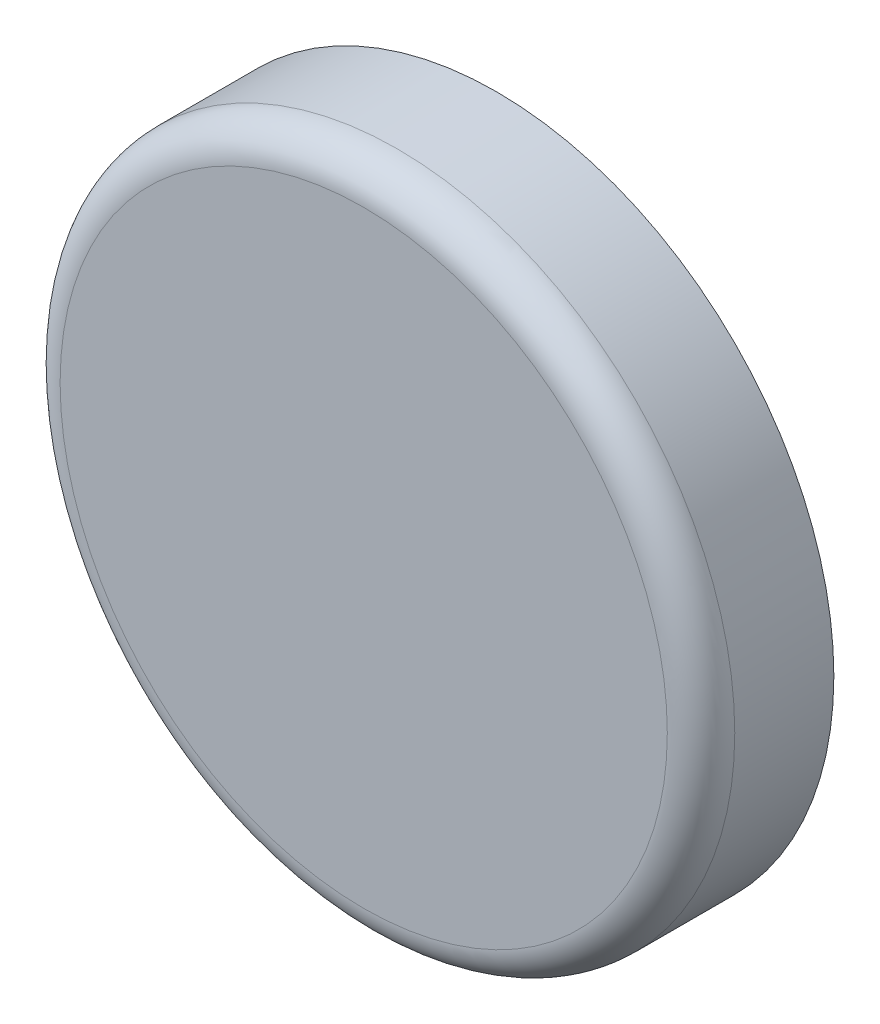
SolidWorks part; units mm, degrees
ref_plane "Front Plane" through (0, 0, 0) normal (0, 0, 1) x (1, 0, 0)
ref_plane "Top Plane" through (0, 0, 0) normal (0, 1, 0) x (1, 0, 0)
ref_plane "Right Plane" through (0, 0, 0) normal (1, 0, 0) x (0, 0, -1)
sketch "Sketch1" plane through (0, 0, 0) normal (0, 0, 1) x (1, 0, 0)
  circle A0 centre (0, 0) radius 12.7
  dimension "D1" = 25.4
extrude "Boss-Extrude1" add sketch "Sketch1" along normal blind 5
sketch "Sketch3" plane through (0, 0, 0) normal (0, 0, -1) x (-1, 0, 0)
  circle A0 centre (0, 0) radius 1.5
  dimension "D1" = 3
extrude "Boss-Extrude2" add sketch "Sketch3" along normal blind 6.35
fillet "Fillet1" radius 1.27 1 edges at (12.7, 0, 5)
